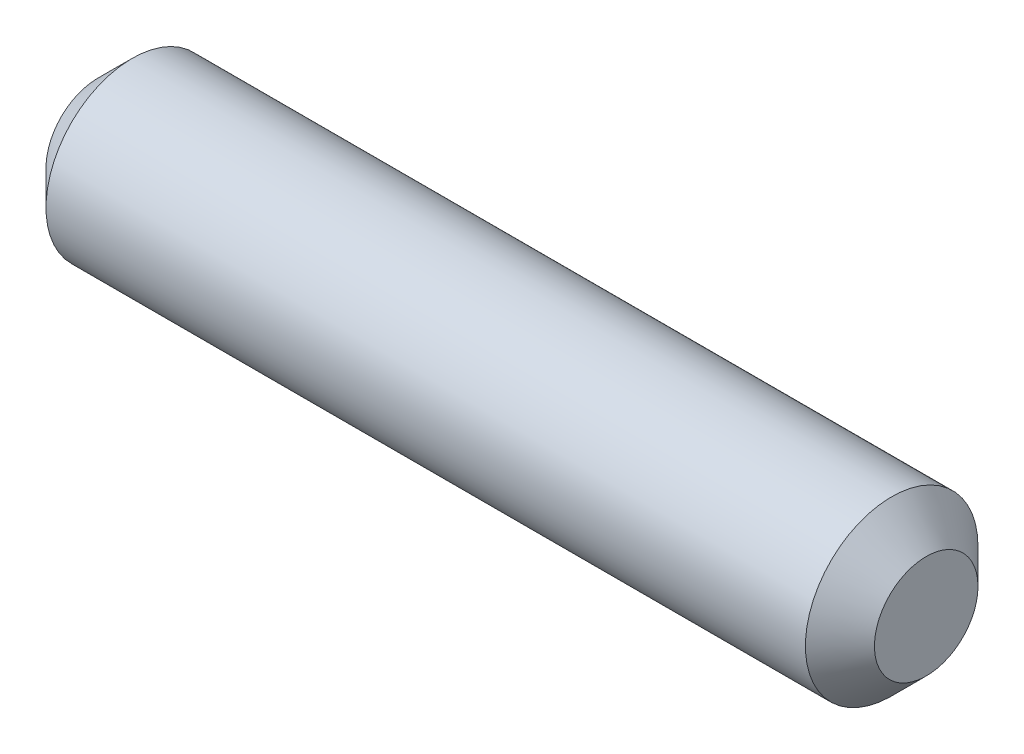
SolidWorks part; units mm, degrees
material "AISI 304"
ref_plane "Front Plane" through (0, 0, 0) normal (0, 0, 1) x (1, 0, 0)
ref_plane "Top Plane" through (0, 0, 0) normal (0, 1, 0) x (1, 0, 0)
ref_plane "Right Plane" through (0, 0, 0) normal (1, 0, 0) x (0, 0, -1)
sketch "Sketch1" plane through (0, 0, 0) normal (1, 0, 0) x (0, 0, -1)
  circle A0 centre (0, 0) radius 1.25
  dimension "D1" = 2.5
extrude "Boss-Extrude1" add sketch "Sketch1" along normal blind 12
chamfer "Chamfer1" distance 0.5 2 edges at (0, 0, -1.25) (12, 0, -1.25)
